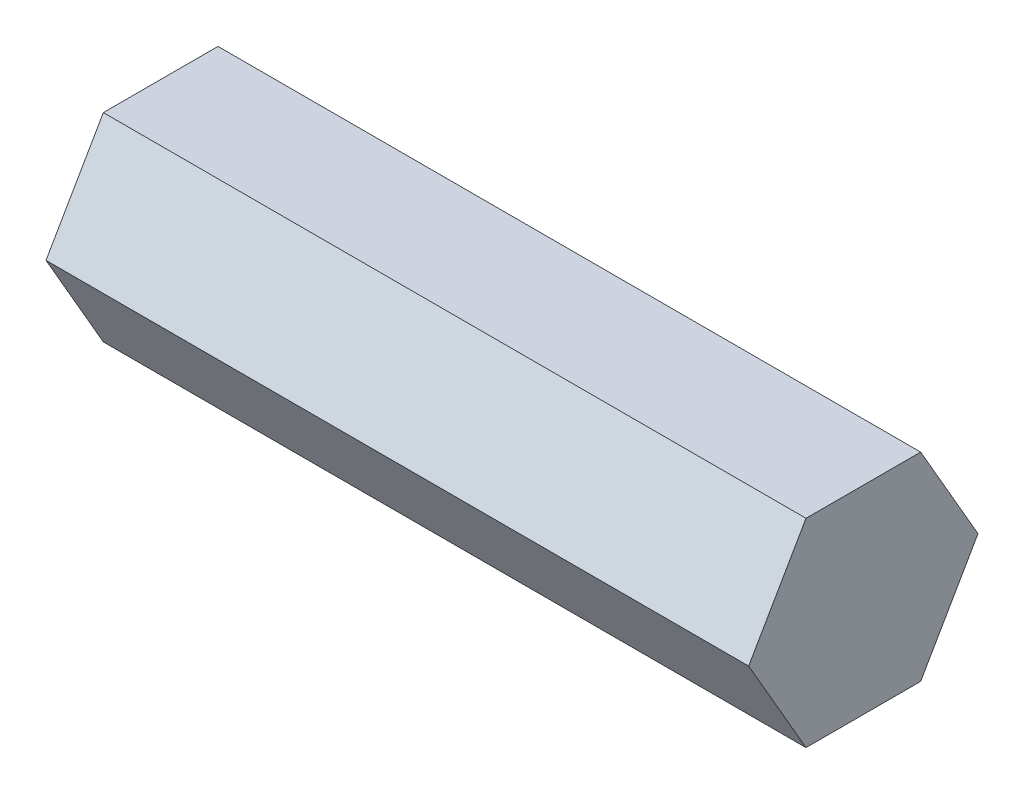
SolidWorks part; units mm, degrees
ref_plane "Alzado" through (0, 0, 0) normal (0, 0, 1) x (1, 0, 0)
ref_plane "Planta" through (0, 0, 0) normal (0, 1, 0) x (1, 0, 0)
ref_plane "Vista lateral" through (0, 0, 0) normal (1, 0, 0) x (0, 0, -1)
sketch "Croquis2" plane through (0, 0, 0) normal (1, 0, 0) x (0, 0, -1)
  line L1 (7.3323, 0) -> (3.6662, 6.35)
  line L2 (3.6662, 6.35) -> (-3.6662, 6.35)
  line L3 (-3.6662, 6.35) -> (-7.3323, 0)
  line L4 (-7.3323, 0) -> (-3.6662, -6.35)
  line L5 (-3.6662, -6.35) -> (3.6662, -6.35)
  line L6 (3.6662, -6.35) -> (7.3323, 0)
  circle A0 centre (0, 0) radius 6.35 construction
  dimension "D1" = 12.7
extrude "Saliente-Extruir1" add sketch "Croquis2" along normal blind 44.935
